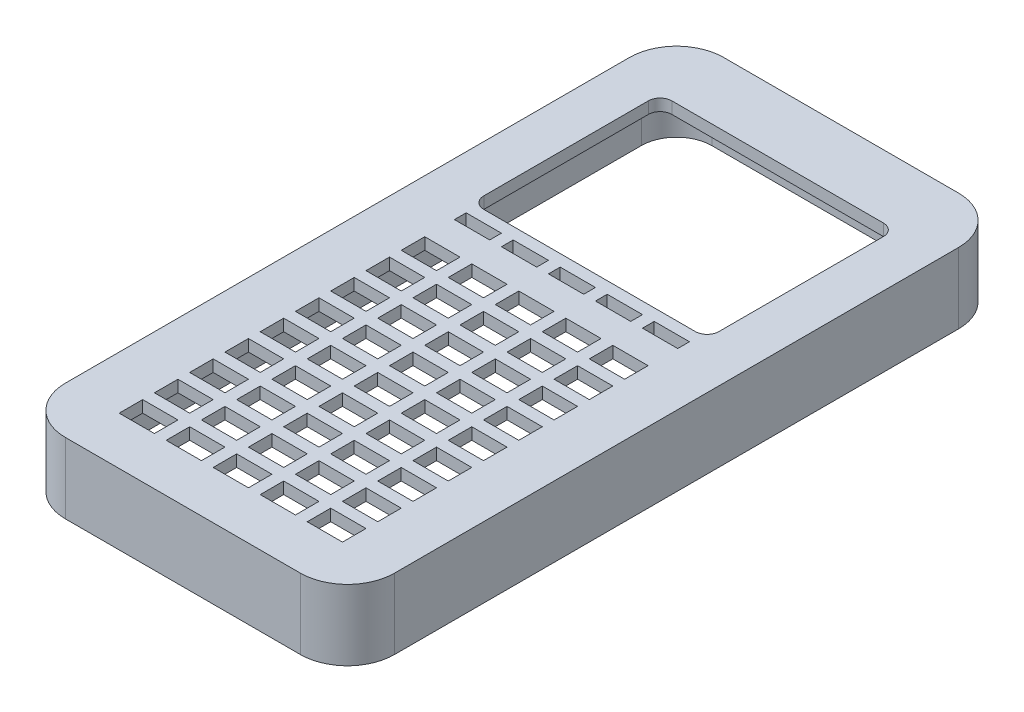
SolidWorks part; units mm, degrees
ref_plane "Front Plane" through (0, 0, 0) normal (0, 0, 1) x (1, 0, 0)
ref_plane "Top Plane" through (0, 0, 0) normal (0, 1, 0) x (1, 0, 0)
ref_plane "Right Plane" through (0, 0, 0) normal (1, 0, 0) x (0, 0, -1)
sketch "Sketch1" plane through (0, 0, 0) normal (0, 1, 0) x (1, 0, 0)
  line L0 (31.75, 0) -> (-31.75, 0)
  line L1 (-44.45, -12.7) -> (-44.45, -165.1)
  line L2 (-31.75, -177.8) -> (31.75, -177.8)
  line L3 (44.45, -165.1) -> (44.45, -12.7)
  line L4 (0, 0) -> (0, -75.5815) construction
  arc A0 (-31.75, 0) -> (-44.45, -12.7) centre (-31.75, -12.7) ccw
  arc A1 (31.75, -177.8) -> (44.45, -165.1) centre (31.75, -165.1) ccw
  arc A2 (-44.45, -165.1) -> (-31.75, -177.8) centre (-31.75, -165.1) ccw
  arc A3 (31.75, 0) -> (44.45, -12.7) centre (31.75, -12.7) cw
  point P4 (0, 0)
  point P9 (-44.45, 0)
  point P14 (-44.45, -177.8)
  point P17 (44.45, 0)
  point P23 (0, -24.4187)
  dimension "D3" = 12.7
  dimension "D4" = 12.7
  dimension "D1" = 88.9
  dimension "D2" = 177.8
extrude "Boss-Extrude1" add sketch "Sketch1" along normal blind 19.05
shell "Shell1" thickness 3.175
sketch "Sketch2" plane through (0, 19.05, 0) normal (0, 1, 0) x (1, 0, 0)
  line L0 (0, 0) -> (0, -73.3558) construction
  line L1 (31.75, 0) -> (-31.75, 0) construction
  line L2 (28.575, -17.145) -> (-28.575, -17.145)
  line L3 (31.75, -20.32) -> (31.75, -64.77)
  line L4 (28.575, -67.945) -> (-28.575, -67.945)
  line L5 (-31.75, -20.32) -> (-31.75, -64.77)
  line L6 (31.75, -17.145) -> (-31.75, -67.945) construction
  line L7 (31.75, -67.945) -> (-31.75, -17.145) construction
  line L8 (-44.45, -12.7) -> (-44.45, -165.1) construction
  line L9 (-30.1625, -71.12) -> (-20.6375, -71.12)
  line L10 (-30.1625, -71.12) -> (-30.1625, -74.295)
  line L11 (-30.1625, -74.295) -> (-20.6375, -74.295)
  line L12 (-20.6375, -71.12) -> (-20.6375, -74.295)
  line L13 (-31.75, -177.8) -> (31.75, -177.8) construction
  line L14 (-30.1625, -158.5051) -> (-20.6375, -158.5051)
  line L15 (-30.1625, -158.5051) -> (-30.1625, -164.8551)
  line L16 (-30.1625, -164.8551) -> (-20.6375, -164.8551)
  line L17 (-20.6375, -158.5051) -> (-20.6375, -164.8551)
  line L18 (-17.4625, -158.5051) -> (-17.4625, -164.8551)
  line L19 (-17.4625, -158.5051) -> (-7.9375, -158.5051)
  line L20 (-7.9375, -158.5051) -> (-7.9375, -164.8551)
  line L21 (-17.4625, -164.8551) -> (-7.9375, -164.8551)
  line L22 (-4.7625, -158.5051) -> (-4.7625, -164.8551)
  line L23 (-4.7625, -158.5051) -> (4.7625, -158.5051)
  line L24 (4.7625, -158.5051) -> (4.7625, -164.8551)
  line L25 (-4.7625, -164.8551) -> (4.7625, -164.8551)
  line L26 (7.9375, -158.5051) -> (7.9375, -164.8551)
  line L27 (7.9375, -158.5051) -> (17.4625, -158.5051)
  line L28 (17.4625, -158.5051) -> (17.4625, -164.8551)
  line L29 (7.9375, -164.8551) -> (17.4625, -164.8551)
  line L30 (20.6375, -158.5051) -> (20.6375, -164.8551)
  line L31 (20.6375, -158.5051) -> (30.1625, -158.5051)
  line L32 (30.1625, -158.5051) -> (30.1625, -164.8551)
  line L33 (20.6375, -164.8551) -> (30.1625, -164.8551)
  line L34 (-17.4625, -148.9801) -> (-17.4625, -155.3301)
  line L35 (-17.4625, -148.9801) -> (-7.9375, -148.9801)
  line L36 (-7.9375, -148.9801) -> (-7.9375, -155.3301)
  line L37 (-17.4625, -155.3301) -> (-7.9375, -155.3301)
  line L38 (-4.7625, -148.9801) -> (-4.7625, -155.3301)
  line L39 (-4.7625, -148.9801) -> (4.7625, -148.9801)
  line L40 (4.7625, -148.9801) -> (4.7625, -155.3301)
  line L41 (-4.7625, -155.3301) -> (4.7625, -155.3301)
  line L42 (7.9375, -148.9801) -> (7.9375, -155.3301)
  line L43 (7.9375, -148.9801) -> (17.4625, -148.9801)
  line L44 (17.4625, -148.9801) -> (17.4625, -155.3301)
  line L45 (7.9375, -155.3301) -> (17.4625, -155.3301)
  line L46 (20.6375, -148.9801) -> (20.6375, -155.3301)
  line L47 (20.6375, -148.9801) -> (30.1625, -148.9801)
  line L48 (30.1625, -148.9801) -> (30.1625, -155.3301)
  line L49 (20.6375, -155.3301) -> (30.1625, -155.3301)
  line L50 (-17.4625, -139.4551) -> (-17.4625, -145.8051)
  line L51 (-17.4625, -139.4551) -> (-7.9375, -139.4551)
  line L52 (-7.9375, -139.4551) -> (-7.9375, -145.8051)
  line L53 (-17.4625, -145.8051) -> (-7.9375, -145.8051)
  line L54 (-4.7625, -139.4551) -> (-4.7625, -145.8051)
  line L55 (-4.7625, -139.4551) -> (4.7625, -139.4551)
  line L56 (4.7625, -139.4551) -> (4.7625, -145.8051)
  line L57 (-4.7625, -145.8051) -> (4.7625, -145.8051)
  line L58 (7.9375, -139.4551) -> (7.9375, -145.8051)
  line L59 (7.9375, -139.4551) -> (17.4625, -139.4551)
  line L60 (17.4625, -139.4551) -> (17.4625, -145.8051)
  line L61 (7.9375, -145.8051) -> (17.4625, -145.8051)
  line L62 (20.6375, -139.4551) -> (20.6375, -145.8051)
  line L63 (20.6375, -139.4551) -> (30.1625, -139.4551)
  line L64 (30.1625, -139.4551) -> (30.1625, -145.8051)
  line L65 (20.6375, -145.8051) -> (30.1625, -145.8051)
  line L66 (-17.4625, -129.9301) -> (-17.4625, -136.2801)
  line L67 (-17.4625, -129.9301) -> (-7.9375, -129.9301)
  line L68 (-7.9375, -129.9301) -> (-7.9375, -136.2801)
  line L69 (-17.4625, -136.2801) -> (-7.9375, -136.2801)
  line L70 (-4.7625, -129.9301) -> (-4.7625, -136.2801)
  line L71 (-4.7625, -129.9301) -> (4.7625, -129.9301)
  line L72 (4.7625, -129.9301) -> (4.7625, -136.2801)
  line L73 (-4.7625, -136.2801) -> (4.7625, -136.2801)
  line L74 (7.9375, -129.9301) -> (7.9375, -136.2801)
  line L75 (7.9375, -129.9301) -> (17.4625, -129.9301)
  line L76 (17.4625, -129.9301) -> (17.4625, -136.2801)
  line L77 (7.9375, -136.2801) -> (17.4625, -136.2801)
  line L78 (20.6375, -129.9301) -> (20.6375, -136.2801)
  line L79 (20.6375, -129.9301) -> (30.1625, -129.9301)
  line L80 (30.1625, -129.9301) -> (30.1625, -136.2801)
  line L81 (20.6375, -136.2801) -> (30.1625, -136.2801)
  line L82 (-17.4625, -120.4051) -> (-17.4625, -126.7551)
  line L83 (-17.4625, -120.4051) -> (-7.9375, -120.4051)
  line L84 (-7.9375, -120.4051) -> (-7.9375, -126.7551)
  line L85 (-17.4625, -126.7551) -> (-7.9375, -126.7551)
  line L86 (-4.7625, -120.4051) -> (-4.7625, -126.7551)
  line L87 (-4.7625, -120.4051) -> (4.7625, -120.4051)
  line L88 (4.7625, -120.4051) -> (4.7625, -126.7551)
  line L89 (-4.7625, -126.7551) -> (4.7625, -126.7551)
  line L90 (7.9375, -120.4051) -> (7.9375, -126.7551)
  line L91 (7.9375, -120.4051) -> (17.4625, -120.4051)
  line L92 (17.4625, -120.4051) -> (17.4625, -126.7551)
  line L93 (7.9375, -126.7551) -> (17.4625, -126.7551)
  line L94 (20.6375, -120.4051) -> (20.6375, -126.7551)
  line L95 (20.6375, -120.4051) -> (30.1625, -120.4051)
  line L96 (30.1625, -120.4051) -> (30.1625, -126.7551)
  line L97 (20.6375, -126.7551) -> (30.1625, -126.7551)
  line L98 (-17.4625, -110.8801) -> (-17.4625, -117.2301)
  line L99 (-17.4625, -110.8801) -> (-7.9375, -110.8801)
  line L100 (-7.9375, -110.8801) -> (-7.9375, -117.2301)
  line L101 (-17.4625, -117.2301) -> (-7.9375, -117.2301)
  line L102 (-4.7625, -110.8801) -> (-4.7625, -117.2301)
  line L103 (-4.7625, -110.8801) -> (4.7625, -110.8801)
  line L104 (4.7625, -110.8801) -> (4.7625, -117.2301)
  line L105 (-4.7625, -117.2301) -> (4.7625, -117.2301)
  line L106 (7.9375, -110.8801) -> (7.9375, -117.2301)
  line L107 (7.9375, -110.8801) -> (17.4625, -110.8801)
  line L108 (17.4625, -110.8801) -> (17.4625, -117.2301)
  line L109 (7.9375, -117.2301) -> (17.4625, -117.2301)
  line L110 (20.6375, -110.8801) -> (20.6375, -117.2301)
  line L111 (20.6375, -110.8801) -> (30.1625, -110.8801)
  line L112 (30.1625, -110.8801) -> (30.1625, -117.2301)
  line L113 (20.6375, -117.2301) -> (30.1625, -117.2301)
  line L114 (-17.4625, -101.3551) -> (-17.4625, -107.7051)
  line L115 (-17.4625, -101.3551) -> (-7.9375, -101.3551)
  line L116 (-7.9375, -101.3551) -> (-7.9375, -107.7051)
  line L117 (-17.4625, -107.7051) -> (-7.9375, -107.7051)
  line L118 (-4.7625, -101.3551) -> (-4.7625, -107.7051)
  line L119 (-4.7625, -101.3551) -> (4.7625, -101.3551)
  line L120 (4.7625, -101.3551) -> (4.7625, -107.7051)
  line L121 (-4.7625, -107.7051) -> (4.7625, -107.7051)
  line L122 (7.9375, -101.3551) -> (7.9375, -107.7051)
  line L123 (7.9375, -101.3551) -> (17.4625, -101.3551)
  line L124 (17.4625, -101.3551) -> (17.4625, -107.7051)
  line L125 (7.9375, -107.7051) -> (17.4625, -107.7051)
  line L126 (20.6375, -101.3551) -> (20.6375, -107.7051)
  line L127 (20.6375, -101.3551) -> (30.1625, -101.3551)
  line L128 (30.1625, -101.3551) -> (30.1625, -107.7051)
  line L129 (20.6375, -107.7051) -> (30.1625, -107.7051)
  line L130 (-17.4625, -91.8301) -> (-17.4625, -98.1801)
  line L131 (-17.4625, -91.8301) -> (-7.9375, -91.8301)
  line L132 (-7.9375, -91.8301) -> (-7.9375, -98.1801)
  line L133 (-17.4625, -98.1801) -> (-7.9375, -98.1801)
  line L134 (-4.7625, -91.8301) -> (-4.7625, -98.1801)
  line L135 (-4.7625, -91.8301) -> (4.7625, -91.8301)
  line L136 (4.7625, -91.8301) -> (4.7625, -98.1801)
  line L137 (-4.7625, -98.1801) -> (4.7625, -98.1801)
  line L138 (7.9375, -91.8301) -> (7.9375, -98.1801)
  line L139 (7.9375, -91.8301) -> (17.4625, -91.8301)
  line L140 (17.4625, -91.8301) -> (17.4625, -98.1801)
  line L141 (7.9375, -98.1801) -> (17.4625, -98.1801)
  line L142 (20.6375, -91.8301) -> (20.6375, -98.1801)
  line L143 (20.6375, -91.8301) -> (30.1625, -91.8301)
  line L144 (30.1625, -91.8301) -> (30.1625, -98.1801)
  line L145 (20.6375, -98.1801) -> (30.1625, -98.1801)
  line L146 (-17.4625, -82.3051) -> (-17.4625, -88.6551)
  line L147 (-17.4625, -82.3051) -> (-7.9375, -82.3051)
  line L148 (-7.9375, -82.3051) -> (-7.9375, -88.6551)
  line L149 (-17.4625, -88.6551) -> (-7.9375, -88.6551)
  line L150 (-4.7625, -82.3051) -> (-4.7625, -88.6551)
  line L151 (-4.7625, -82.3051) -> (4.7625, -82.3051)
  line L152 (4.7625, -82.3051) -> (4.7625, -88.6551)
  line L153 (-4.7625, -88.6551) -> (4.7625, -88.6551)
  line L154 (7.9375, -82.3051) -> (7.9375, -88.6551)
  line L155 (7.9375, -82.3051) -> (17.4625, -82.3051)
  line L156 (17.4625, -82.3051) -> (17.4625, -88.6551)
  line L157 (7.9375, -88.6551) -> (17.4625, -88.6551)
  line L158 (20.6375, -82.3051) -> (20.6375, -88.6551)
  line L159 (20.6375, -82.3051) -> (30.1625, -82.3051)
  line L160 (30.1625, -82.3051) -> (30.1625, -88.6551)
  line L161 (20.6375, -88.6551) -> (30.1625, -88.6551)
  line L162 (-30.1625, -148.9801) -> (-30.1625, -155.3301)
  line L163 (-30.1625, -148.9801) -> (-20.6375, -148.9801)
  line L164 (-20.6375, -148.9801) -> (-20.6375, -155.3301)
  line L165 (-30.1625, -155.3301) -> (-20.6375, -155.3301)
  line L166 (-30.1625, -139.4551) -> (-30.1625, -145.8051)
  line L167 (-30.1625, -139.4551) -> (-20.6375, -139.4551)
  line L168 (-20.6375, -139.4551) -> (-20.6375, -145.8051)
  line L169 (-30.1625, -145.8051) -> (-20.6375, -145.8051)
  line L170 (-30.1625, -129.9301) -> (-30.1625, -136.2801)
  line L171 (-30.1625, -129.9301) -> (-20.6375, -129.9301)
  line L172 (-20.6375, -129.9301) -> (-20.6375, -136.2801)
  line L173 (-30.1625, -136.2801) -> (-20.6375, -136.2801)
  line L174 (-30.1625, -120.4051) -> (-30.1625, -126.7551)
  line L175 (-30.1625, -120.4051) -> (-20.6375, -120.4051)
  line L176 (-20.6375, -120.4051) -> (-20.6375, -126.7551)
  line L177 (-30.1625, -126.7551) -> (-20.6375, -126.7551)
  line L178 (-30.1625, -110.8801) -> (-30.1625, -117.2301)
  line L179 (-30.1625, -110.8801) -> (-20.6375, -110.8801)
  line L180 (-20.6375, -110.8801) -> (-20.6375, -117.2301)
  line L181 (-30.1625, -117.2301) -> (-20.6375, -117.2301)
  line L182 (-30.1625, -101.3551) -> (-30.1625, -107.7051)
  line L183 (-30.1625, -101.3551) -> (-20.6375, -101.3551)
  line L184 (-20.6375, -101.3551) -> (-20.6375, -107.7051)
  line L185 (-30.1625, -107.7051) -> (-20.6375, -107.7051)
  line L186 (-30.1625, -91.8301) -> (-30.1625, -98.1801)
  line L187 (-30.1625, -91.8301) -> (-20.6375, -91.8301)
  line L188 (-20.6375, -91.8301) -> (-20.6375, -98.1801)
  line L189 (-30.1625, -98.1801) -> (-20.6375, -98.1801)
  line L190 (-30.1625, -82.3051) -> (-30.1625, -88.6551)
  line L191 (-30.1625, -82.3051) -> (-20.6375, -82.3051)
  line L192 (-20.6375, -82.3051) -> (-20.6375, -88.6551)
  line L193 (-30.1625, -88.6551) -> (-20.6375, -88.6551)
  line L194 (-17.4625, -71.12) -> (-17.4625, -74.295)
  line L195 (-17.4625, -71.12) -> (-7.9375, -71.12)
  line L196 (-7.9375, -71.12) -> (-7.9375, -74.295)
  line L197 (-17.4625, -74.295) -> (-7.9375, -74.295)
  line L198 (-4.7625, -71.12) -> (-4.7625, -74.295)
  line L199 (-4.7625, -71.12) -> (4.7625, -71.12)
  line L200 (4.7625, -71.12) -> (4.7625, -74.295)
  line L201 (-4.7625, -74.295) -> (4.7625, -74.295)
  line L202 (7.9375, -71.12) -> (7.9375, -74.295)
  line L203 (7.9375, -71.12) -> (17.4625, -71.12)
  line L204 (17.4625, -71.12) -> (17.4625, -74.295)
  line L205 (7.9375, -74.295) -> (17.4625, -74.295)
  line L206 (20.6375, -71.12) -> (20.6375, -74.295)
  line L207 (20.6375, -71.12) -> (30.1625, -71.12)
  line L208 (30.1625, -71.12) -> (30.1625, -74.295)
  line L209 (20.6375, -74.295) -> (30.1625, -74.295)
  arc A0 (28.575, -17.145) -> (31.75, -20.32) centre (28.575, -20.32) cw
  arc A1 (31.75, -64.77) -> (28.575, -67.945) centre (28.575, -64.77) cw
  arc A2 (-28.575, -67.945) -> (-31.75, -64.77) centre (-28.575, -64.77) cw
  arc A3 (-28.575, -17.145) -> (-31.75, -20.32) centre (-28.575, -20.32) ccw
  point P3 (0, -42.545)
  dimension "D3" = 3.175
  dimension "D1" = 50.8
  dimension "D2" = 63.5
  dimension "D4" = 17.145
  dimension "D5" = 3.175
  dimension "D6" = 9.525
  dimension "D7" = 3.175
  dimension "D8" = 14.2875
  dimension "D9" = 6.35
  dimension "D10" = 9.525
  dimension "D11" = 14.2875
  dimension "D12" = 12.9449
  dimension "D15" = 3.175
  dimension "D16" = 3.175
  dimension "D17" = 14.2875
  dimension "D18" = 3.175
  dimension "D20" = 3.175
  dimension "D13" = 5
  dimension "D14" = 9
  dimension "D19" = 5
extrude "Cut-Extrude1" cut sketch "Sketch2" against normal blind 19.05
